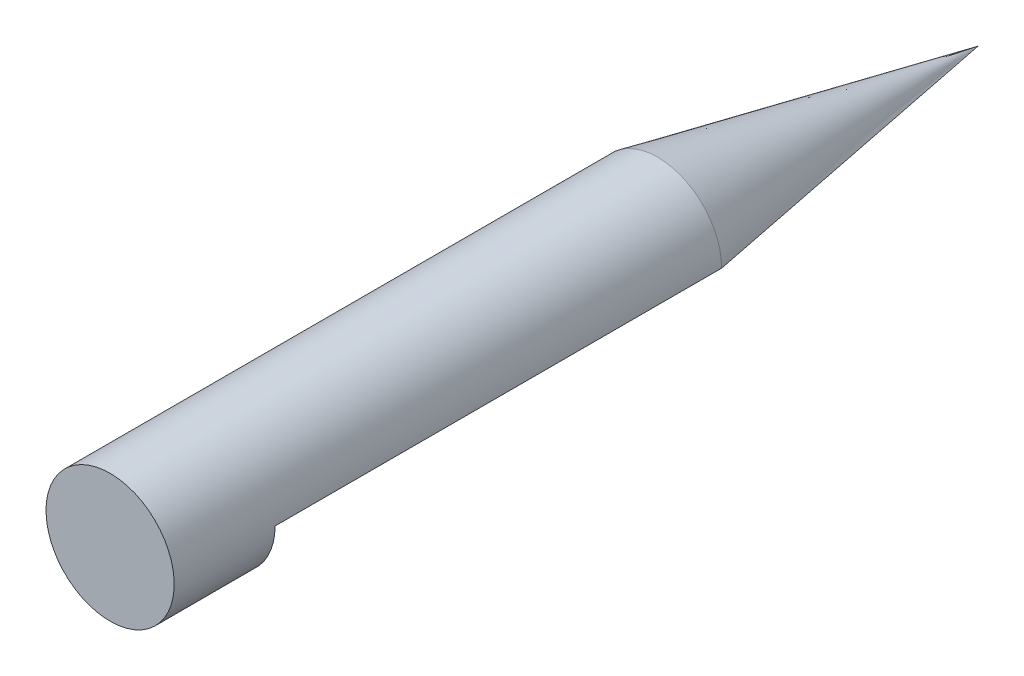
SolidWorks part; units mm, degrees
ref_plane "Front Plane" through (0, 0, 0) normal (0, 0, 1) x (1, 0, 0)
ref_plane "Top Plane" through (0, 0, 0) normal (0, 1, 0) x (1, 0, 0)
ref_plane "Right Plane" through (0, 0, 0) normal (1, 0, 0) x (0, 0, -1)
ref_plane "Plane1" through (0, 0, 0) normal (0, -1, 0) x (1, 0, 0)
sketch "Sketch1" plane through (0, 0, 0) normal (0, -1, 0) x (1, 0, 0)
  line L0 (3.175, -2) -> (0, -2)
  line L1 (0, -2) -> (0, -45)
  line L2 (0, -45) -> (3.175, -29.125)
  line L3 (3.175, -29.125) -> (3.175, -2)
  line L4 (0, -2) -> (0, -45) construction
revolve "Revolve1" add sketch "Sketch1" angle 360 about L4
ref_plane "Plane2" through (0, 0, -7) normal (0, 0, 1) x (1, 0, 0)
sketch "Sketch2" plane through (0, 0, -7) normal (0, 0, 1) x (1, 0, 0)
  line L0 (3.175, 0) -> (-3.175, 0)
  arc A0 (-3.175, 0) -> (3.175, 0) centre (0, 0) ccw
extrude "Cut-Extrude2" cut sketch "Sketch2" against normal blind 40
